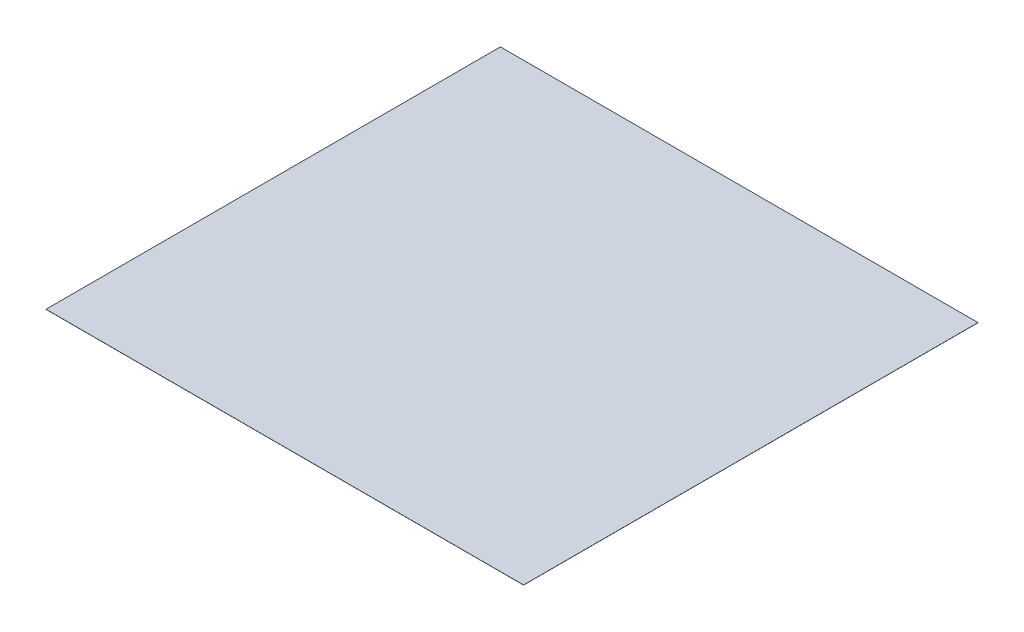
SolidWorks part; units mm, degrees
ref_plane "Front Plane" through (0, 0, 0) normal (0, 0, 1) x (1, 0, 0)
ref_plane "Top Plane" through (0, 0, 0) normal (0, 1, 0) x (1, 0, 0)
ref_plane "Right Plane" through (0, 0, 0) normal (1, 0, 0) x (0, 0, -1)
sketch "Sketch1" plane through (0, 0, 0) normal (0, 1, 0) x (1, 0, 0)
  line L1 (-99.9618, 56.4313) -> (101.8759, 56.4313)
  line L2 (-99.9618, 56.4313) -> (-99.9618, -135.6207)
  line L3 (-99.9618, -135.6207) -> (101.8759, -135.6207)
  line L4 (101.8759, 56.4313) -> (101.8759, -135.6207)
extrude "Boss-Extrude1" add sketch "Sketch1" along normal blind 0.05
sketch "Sketch3" plane through (0, 0.05, 0) normal (0, 1, 0) x (1, 0, 0)
  circle A0 centre (0, -39.5947) radius 6.4609
fillet "Fillet4" [suppressed] radius 0.5
